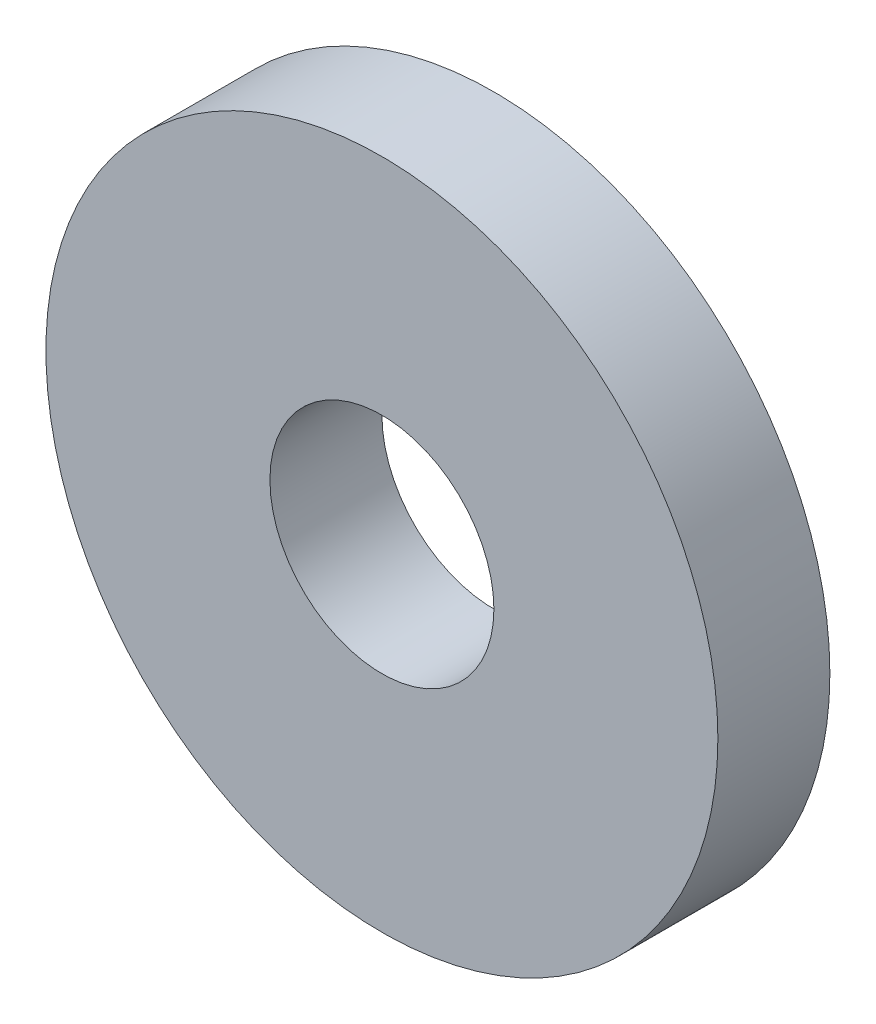
SolidWorks part; units mm, degrees
material "AISI 304"
ref_plane "前视基准面" through (0, 0, 0) normal (0, 0, 1) x (1, 0, 0)
ref_plane "上视基准面" through (0, 0, 0) normal (0, 1, 0) x (1, 0, 0)
ref_plane "右视基准面" through (0, 0, 0) normal (1, 0, 0) x (0, 0, -1)
sketch "草图1" plane through (0, 0, 0) normal (0, 0, 1) x (1, 0, 0)
  circle A0 centre (0, 0) radius 3
  dimension "D1" = 6
extrude "凸台-拉伸1" add sketch "草图1" along normal blind 1
sketch "草图2" plane through (0, 0, 0) normal (0, 1, 0) x (1, 0, 0)
  line L0 (3, 0) -> (-3, 0) construction
  line L1 (1.5, 0) -> (2.5, 0)
  arc A0 (1.5, 0) -> (2.5, 0) centre (2, 0) ccw
  dimension "D1" = 1
  dimension "D2" = 2
revolve "切除-旋转1" cut sketch "草图2" angle 360 about axis through (0, 0, 1) along (0, 0, -1)
sketch "草图3" plane through (0, 0, 0) normal (0, 0, -1) x (-1, 0, 0)
  circle A0 centre (0, 0) radius 1
  dimension "D1" = 2
extrude "切除-拉伸1" cut sketch "草图3" against normal through all
